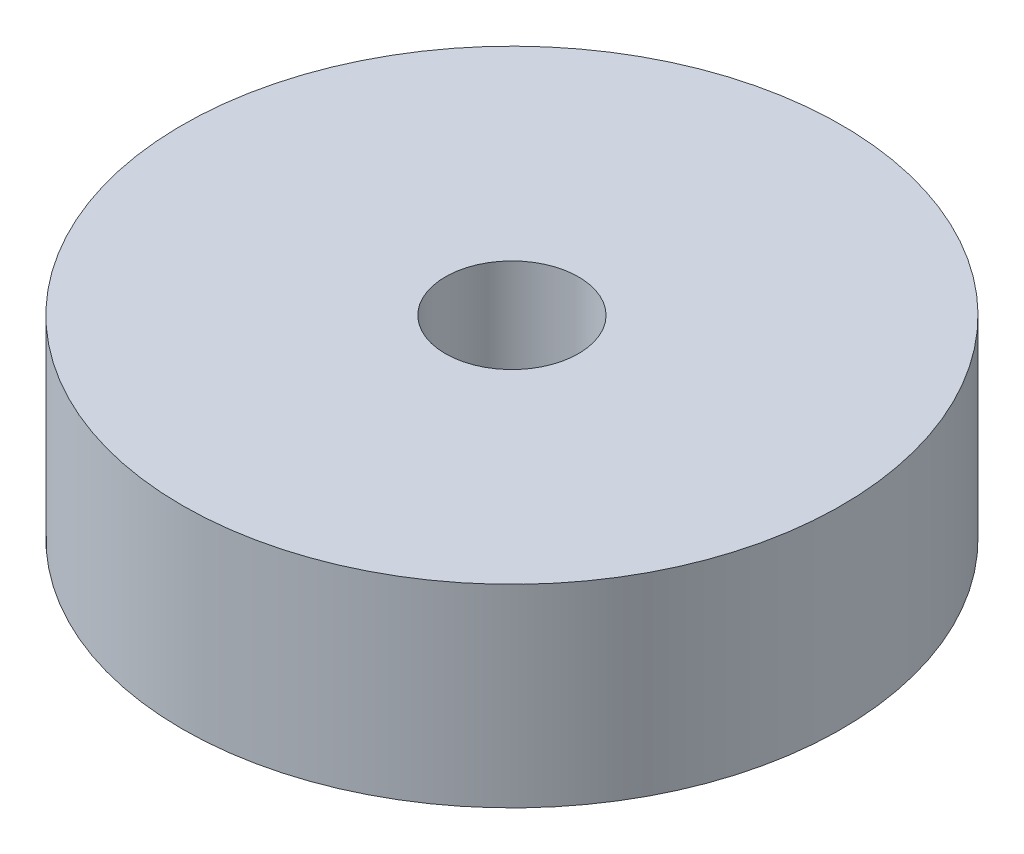
SolidWorks part; units mm, degrees
ref_plane "Front Plane" through (0, 0, 0) normal (0, 0, 1) x (1, 0, 0)
ref_plane "Top Plane" through (0, 0, 0) normal (0, 1, 0) x (1, 0, 0)
ref_plane "Right Plane" through (0, 0, 0) normal (1, 0, 0) x (0, 0, -1)
sketch "Sketch1" plane through (0, 0, 0) normal (0, 1, 0) x (1, 0, 0)
  circle A0 centre (0, 0) radius 9.9
  circle A1 centre (0, 0) radius 2
  dimension "D1" = 19.8
  dimension "D2" = 4
extrude "Boss-Extrude1" add sketch "Sketch1" along normal blind 5.8166
